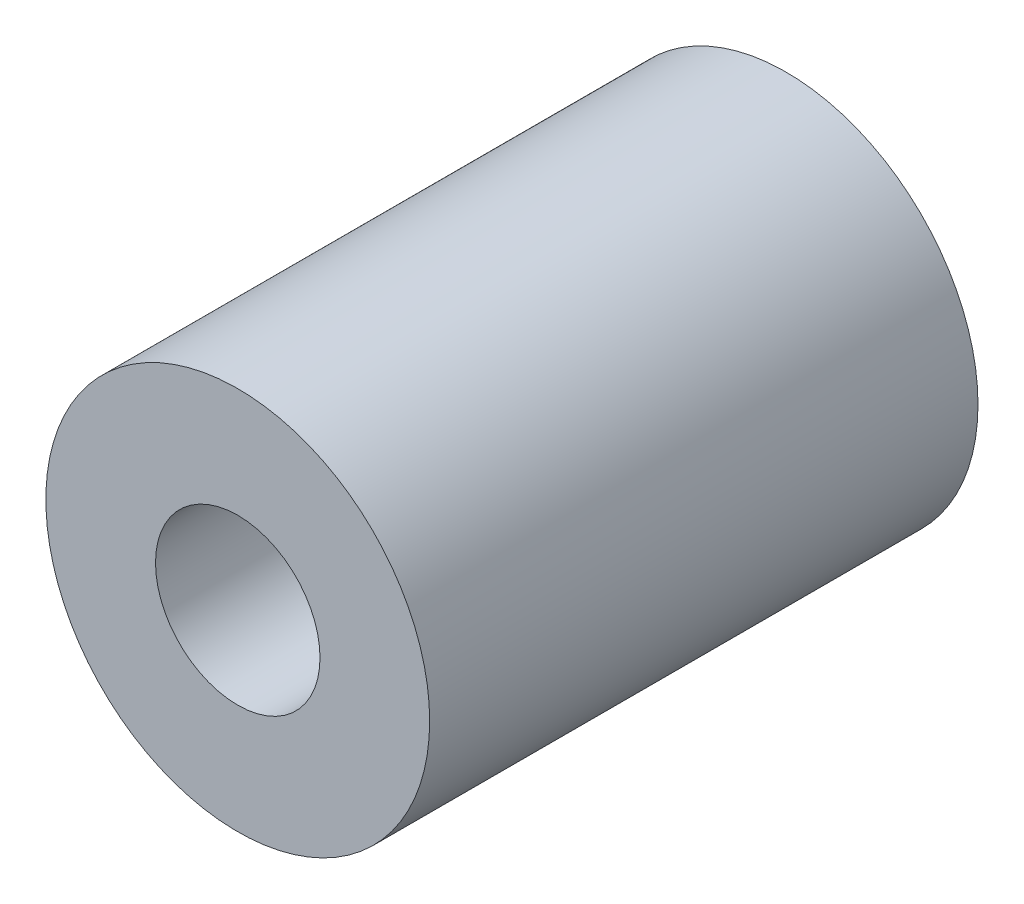
SolidWorks part; units mm, degrees
ref_plane "前基準面" through (0, 0, 0) normal (0, 0, 1) x (1, 0, 0)
ref_plane "上基準面" through (0, 0, 0) normal (0, 1, 0) x (1, 0, 0)
ref_plane "右基準面" through (0, 0, 0) normal (1, 0, 0) x (0, 0, -1)
sketch "草圖1" plane through (0, 0, 0) normal (0, 0, 1) x (1, 0, 0)
  circle A0 centre (0, 0) radius 3.5
  circle A1 centre (0, 0) radius 1.5
  dimension "D1" = 7
  dimension "D2" = 3
extrude "填料-伸長1" add sketch "草圖1" along normal mid plane 10
